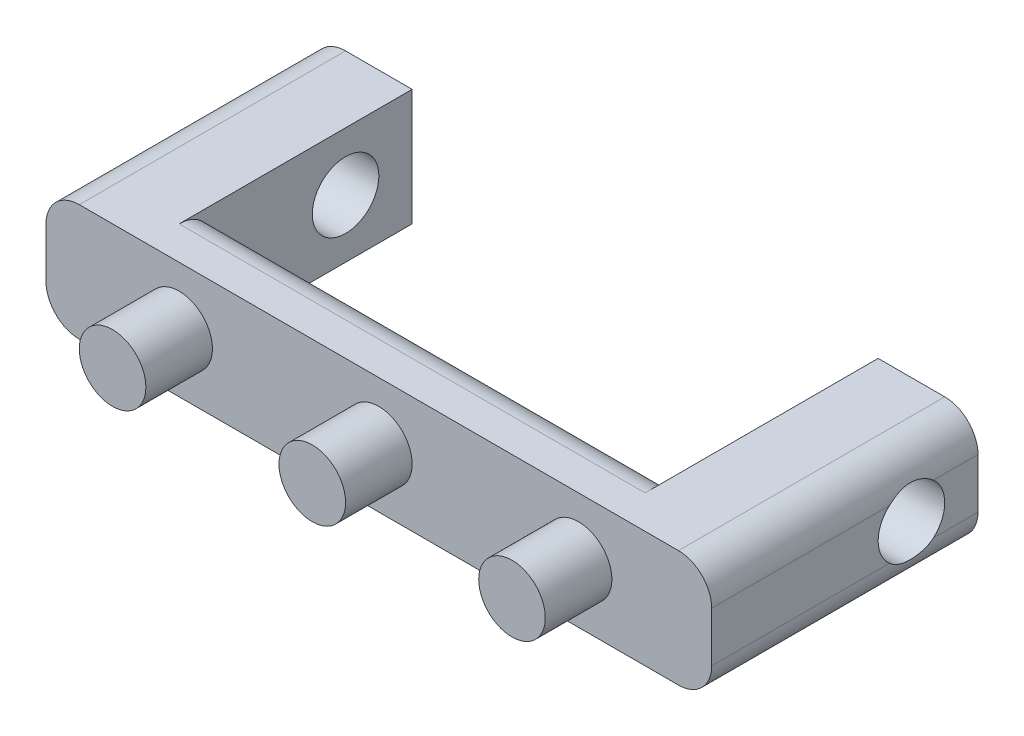
SolidWorks part; units mm, degrees
ref_plane "Front" through (0, 0, 0) normal (0, 0, 1) x (1, 0, 0)
ref_plane "Top" through (0, 0, 0) normal (0, 1, 0) x (1, 0, 0)
ref_plane "Right" through (0, 0, 0) normal (1, 0, 0) x (0, 0, -1)
sketch "Croquis1" plane through (0, 0, 0) normal (0, 1, 0) x (1, 0, 0)
  line L0 (-96.1626, 0) -> (4711.9684, 0) construction
  line L1 (0, -96.1626) -> (0, 4711.9684) construction
  line L2 (10, 0) -> (-10, 0)
  line L3 (-10, 0) -> (-10, 8)
  line L4 (-10, 8) -> (-7, 8)
  line L5 (-7, 8) -> (-7, 2)
  line L6 (-7, 2) -> (7, 2)
  line L7 (10, 0) -> (10, 8)
  line L8 (10, 8) -> (7, 8)
  line L9 (7, 8) -> (7, 2)
  point P10 (0, 2)
  point P14 (0, 0)
  point P15 (0, 2)
  dimension "D1" = 10
  dimension "D2" = 2
  dimension "D3" = 8
  dimension "D4" = 3
extrude "Saliente-Extruir1" add sketch "Croquis1" along normal blind 3.5
sketch "Croquis2" plane through (0, 0, 0) normal (0, 0, 1) x (1, 0, 0)
  line L0 (0, -1000) -> (0, 49000) construction
  line L1 (-1010, 1.75) -> (48990, 1.75) construction
  line L2 (-10, 3.5) -> (-10, 0) construction
  line L3 (6, -1000) -> (6, 49000) construction
  line L4 (-6, -1000) -> (-6, 49000) construction
  circle A0 centre (0, 1.75) radius 1
  circle A1 centre (-6, 1.75) radius 1
  circle A2 centre (6, 1.75) radius 1
  point P8 (-10, 1.75)
  dimension "D3" = 2
  dimension "D4" = 2
  dimension "D1" = 6
  dimension "D2" = 6
extrude "Saliente-Extruir2" add sketch "Croquis2" along normal blind 2
fillet "Redondeo1" radius 1 6 edges at (0, 0, -2) (0, 3.5, -2) (10, 0, -4) (10, 3.5, -4) (-10, 0, -4) (-10, 3.5, -4)
sketch "Croquis3" plane through (-7, 0, 0) normal (1, 0, 0) x (0, 0, -1)
  line L0 (-996, 3.5) -> (49004, 3.5) construction
  line L1 (0, 3.5) -> (8, 3.5) construction
  line L2 (-996, 0) -> (49004, 0) construction
  line L3 (8, 0) -> (0, 0) construction
  line L4 (8, -998.25) -> (8, 49001.75) construction
  line L5 (8, 2.5) -> (8, 1) construction
  line L6 (4, -1000) -> (4, 49000) construction
  line L7 (8, 3.5) -> (-37620.8347, -32921.7304) construction
  line L8 (8, 0) -> (-37620.8347, 32925.2304) construction
  circle A0 centre (6, 1.75) radius 1
  point P5 (4, 3.5)
  point P10 (4, 0)
  point P15 (8, 1.75)
  dimension "D1" = 2
extrude "Cortar-Extruir1" cut sketch "Croquis3" against normal through all
mirror "Simetría3" about plane through (0, 0, 0) normal (1, 0, 0) of "Cortar-Extruir1"
